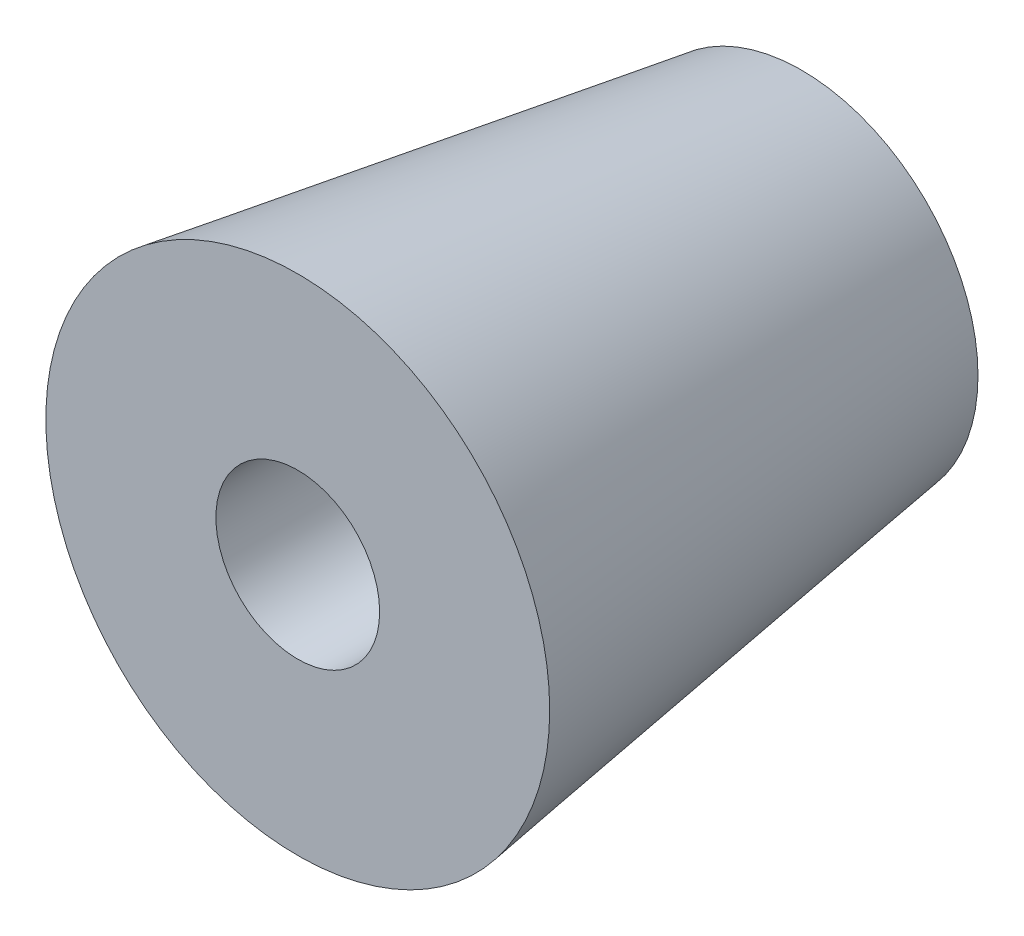
SolidWorks part; units mm, degrees
ref_plane "Front Plane" through (0, 0, 0) normal (0, 0, 1) x (1, 0, 0)
ref_plane "Top Plane" through (0, 0, 0) normal (0, 1, 0) x (1, 0, 0)
ref_plane "Right Plane" through (0, 0, 0) normal (1, 0, 0) x (0, 0, -1)
sketch "Sketch1" plane through (0, 0, 0) normal (0, 0, 1) x (1, 0, 0)
  circle A0 centre (484.4535, 15.7062) radius 20
  dimension "D1" = 40
extrude "Boss-Extrude1" add sketch "Sketch1" against normal blind 40 draft 8.53
sketch "Sketch2" plane through (0, 0, 0) normal (0, 0, 1) x (1, 0, 0)
  circle A0 centre (484.4535, 15.7062) radius 6.5
  dimension "D1" = 13
extrude "Cut-Extrude1" cut sketch "Sketch2" against normal through all
